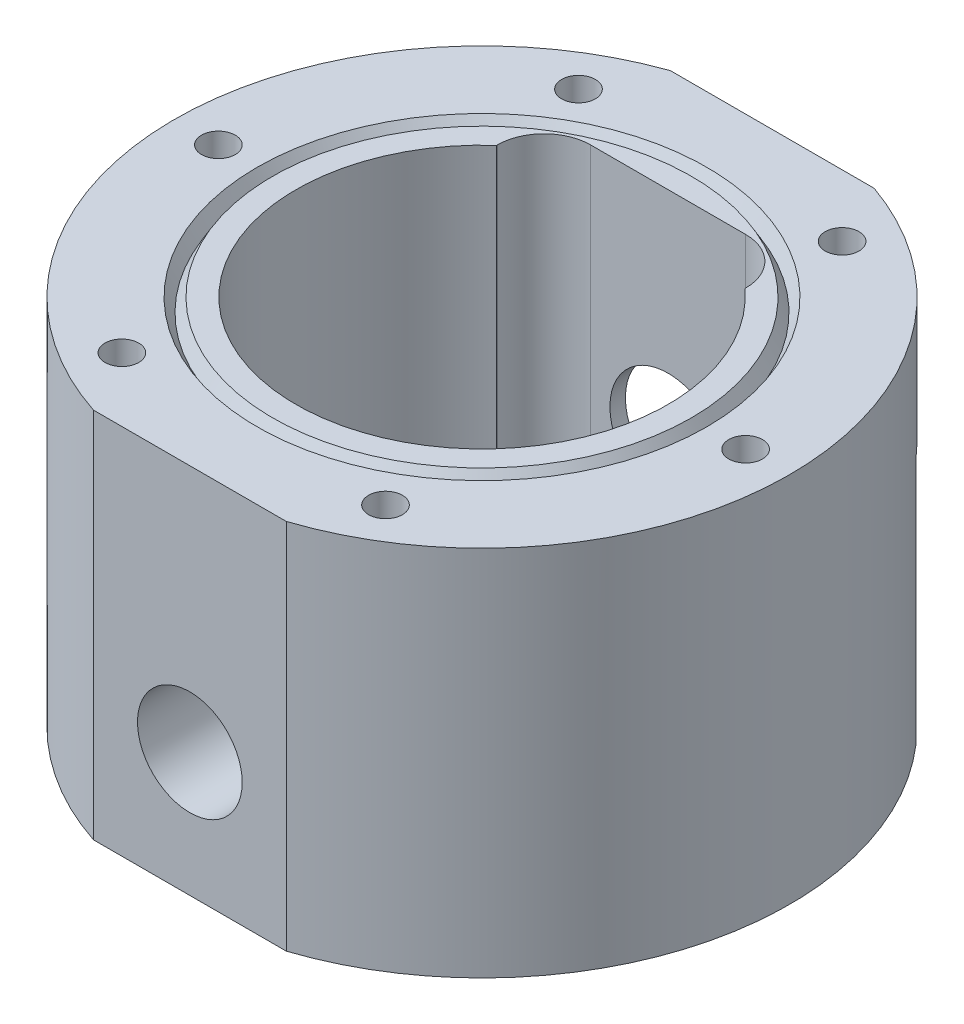
SolidWorks part; units mm, degrees
material "6061-T6 (SS)"
ref_plane "Front Plane" through (0, 0, 0) normal (0, 0, 1) x (1, 0, 0)
ref_plane "Top Plane" through (0, 0, 0) normal (0, 1, 0) x (1, 0, 0)
ref_plane "Right Plane" through (0, 0, 0) normal (1, 0, 0) x (0, 0, -1)
sketch "Sketch1" plane through (0, 0, 0) normal (0, 0, 1) x (1, 0, 0)
  line L0 (0, -582.0391) -> (0, 28519.9157) construction
  line L1 (19.05, 0) -> (19.05, -31.75)
  line L2 (19.05, -31.75) -> (0, -31.75)
  line L3 (0, -31.75) -> (0, -38.1)
  line L4 (0, -38.1) -> (31.496, -38.1)
  line L5 (31.496, -38.1) -> (31.496, 0)
  line L6 (31.496, 0) -> (23.0187, 0)
  line L7 (21.4312, 0) -> (22.225, -1.3748)
  line L8 (22.225, -1.3748) -> (23.0187, 0)
  line L9 (21.4312, 0) -> (19.05, 0)
  dimension "D1" = 31.75
  dimension "D2" = 62.992
  dimension "D3" = 38.1
  dimension "D4" = 38.1
  dimension "D5" = 44.45
  dimension "D6" = 60
  dimension "D7" = 1.5875
revolve "Revolve1" add sketch "Sketch1" angle 360 about L0
sketch "Sketch2" plane through (0, 0, 0) normal (0, 1, 0) x (1, 0, 0)
  line L0 (-10.4326, 29.718) -> (10.4326, 29.718)
  circle A0 centre (0, 0) radius 31.496 construction
  arc A1 (10.4326, 29.718) -> (-10.4326, 29.718) centre (0, 0) ccw
  dimension "D1" = 61.214
extrude "Cut-Extrude1" cut sketch "Sketch2" against normal through all
hole_wizard "#8-32 Tapped Hole1" positions "Sketch3" profile "Sketch5" tap size "#8-32" standard "ANSI Inch"
sketch "Sketch3" plane through (0, 0, 0) normal (0, 1, 0) x (1, 0, 0)
  line L0 (-13.4937, 23.3719) -> (0, 0) construction
  line L1 (0, 0) -> (0, 26.9875) construction
  circle A0 centre (0, 0) radius 26.9875
  point P5 (-13.4937, 23.3719)
  dimension "D1" = 53.975
  dimension "D2" = 30
sketch "Sketch5" plane through (-13.4937, 0, -23.3719) normal (1, 0, 0) x (0, 0, 1)
  line L0 (0, 0) -> (0, 18.2082)
  line L1 (0, 18.2082) -> (1.7272, 17.1704)
  line L2 (1.7272, 17.1704) -> (1.7272, 0)
  line L5 (1.7272, 0) -> (0, 0)
  line L10 (0, 18.2082) -> (-1.7272, 17.1704) construction
  line L11 (0, -6.35) -> (0, 107.95) construction
  dimension "Tap Drill Dia." = 3.4544
  dimension "Tap Drill Depth" = 17.1704
  dimension "Drill Angle" = 118
cosmetic thread "Hole Thread1" parameters "D1"=13.208, "D2"=4.1656
pattern_circular "CirPattern1" count 6 over 360 about axis through (0, 0, 0) along (0, 1, 0) of "#8-32 Tapped Hole1"
sketch "Sketch11" plane through (0, -38.1, 0) normal (0, -1, 0) x (1, 0, 0)
  circle A0 centre (0, 0) radius 5.9531
  dimension "D1" = 11.9062
extrude "Cut-Extrude3" cut sketch "Sketch11" against normal through all
hole_wizard "#4-40 Tapped Hole2" positions "Sketch14" profile "Sketch15" tap size "#4-40" standard "ANSI Inch" end condition through all
sketch "Sketch14" plane through (0, -38.1, 0) normal (0, -1, 0) x (-1, 0, 0)
  line L0 (6.35, -6.35) -> (-6.35, 6.35) construction
  line L3 (-6.35, -6.35) -> (6.35, 6.35) construction
  point P0 (6.35, -6.35)
  point P2 (-6.35, -6.35)
  point P4 (-6.35, 6.35)
  point P6 (6.35, 6.35)
  dimension "D1" = 12.7
  dimension "D2" = 12.7
sketch "Sketch15" plane through (-6.35, -38.1, 6.35) normal (1, 0, 0) x (0, 0, -1)
  line L0 (0, 0) -> (0, 38.1)
  line L1 (0, 38.1) -> (1.1303, 38.1)
  line L2 (1.1303, 38.1) -> (1.1303, 0)
  line L5 (1.1303, 0) -> (0, 0)
  line L11 (0, -6.35) -> (0, 107.95) construction
  dimension "Thru Tap Drill Dia." = 2.2606
  dimension "Thru Tap Drill Depth" = 38.1
cosmetic thread "Hole Thread6" parameters "D2"=2.8448
cosmetic thread "Hole Thread7" parameters "D2"=2.8448
cosmetic thread "Hole Thread8" parameters "D2"=2.8448
cosmetic thread "Hole Thread9" parameters "D2"=2.8448
sketch "Sketch16" plane through (0, -38.1, 0) normal (0, -1, 0) x (1, 0, 0)
  line L0 (-9.8732, 29.9085) -> (9.8732, 29.9085)
  arc A0 (10.4326, -29.718) -> (-10.4326, -29.718) centre (0, 0) ccw construction
  arc A1 (9.8732, 29.9085) -> (-9.8732, 29.9085) centre (0, 0) ccw
  dimension "D1" = 1.5875
extrude "Cut-Extrude4" cut sketch "Sketch16" against normal through all
hole_wizard "1/2-13 Tapped Hole1" positions "Sketch21" profile "Sketch22" tap size "1/2-13" standard "ANSI Inch"
sketch "Sketch21" plane through (0, 0, 29.9085) normal (0, 0, 1) x (1, 0, 0)
  line L0 (9.8732, -38.1) -> (31.496, -38.1) construction
  point P0 (0, -25.4)
  dimension "D1" = 12.7
cosmetic thread "Hole Thread11" parameters "D1"=11.6276, "D2"=12.7
sketch "Sketch22" plane through (0, -25.4, 29.9085) normal (1, 0, 0) x (0, -1, 0)
  line L0 (0, 0) -> (0, 32.0485)
  line L1 (0, 32.0485) -> (5.3581, 28.829)
  line L2 (5.3581, 28.829) -> (5.3581, 0)
  line L5 (5.3581, 0) -> (0, 0)
  line L10 (0, 32.0485) -> (-5.3581, 28.829) construction
  line L11 (0, -6.35) -> (0, 107.95) construction
  dimension "Tap Drill Dia." = 10.7163
  dimension "Tap Drill Depth" = 28.829
  dimension "Drill Angle" = 118
sketch "Sketch23" plane through (0, 0, -29.718) normal (0, 0, -1) x (-1, 0, 0)
  line L0 (10.4326, 0) -> (-10.4326, 0) construction
  circle A0 centre (0, -22.225) radius 5.9531
  dimension "D1" = 11.9062
  dimension "D2" = 22.225
extrude "Cut-Extrude5" cut sketch "Sketch23" against normal up to next
sketch "Sketch24" plane through (0, 0, 0) normal (0, 1, 0) x (1, 0, 0)
  line L0 (-7.9375, 19.05) -> (7.9375, 19.05)
  line L1 (0, 0) -> (0, 19.05) construction
  line L2 (-12.7, 14.2875) -> (-12.7, 5.7429)
  line L3 (-12.7, 5.7429) -> (12.7, 5.7429)
  line L4 (12.7, 5.7429) -> (12.7, 14.2875)
  arc A0 (-7.9375, 19.05) -> (-12.7, 14.2875) centre (-7.9375, 14.2875) ccw
  arc A1 (12.7, 14.2875) -> (7.9375, 19.05) centre (7.9375, 14.2875) ccw
  circle A2 centre (0, 0) radius 19.05 construction
  dimension "D1" = 4.7625
  dimension "D2" = 15.875
extrude "Cut-Extrude6" cut sketch "Sketch24" against normal up to surface (31.75 mm away) up to face at (-7.4803, -31.75, 6.35)
sketch "Sketch25" plane through (0, 0, -29.718) normal (0, 0, -1) x (-1, 0, 0)
  line L0 (31.496, 0) -> (9.8732, 0) construction
  line L1 (40.2772, -39.8569) -> (-47.7164, -39.8569)
  line L2 (40.2772, -39.8569) -> (40.2772, -12.7)
  line L3 (40.2772, -12.7) -> (-47.7164, -12.7)
  line L4 (-47.7164, -39.8569) -> (-47.7164, -12.7)
  dimension "D1" = 12.7
extrude "Cut-Extrude7" cut sketch "Sketch25" against normal offset from surface (9.0805 mm away) 1.5875 up to face at (-5.9531, -22.225, -19.05)
